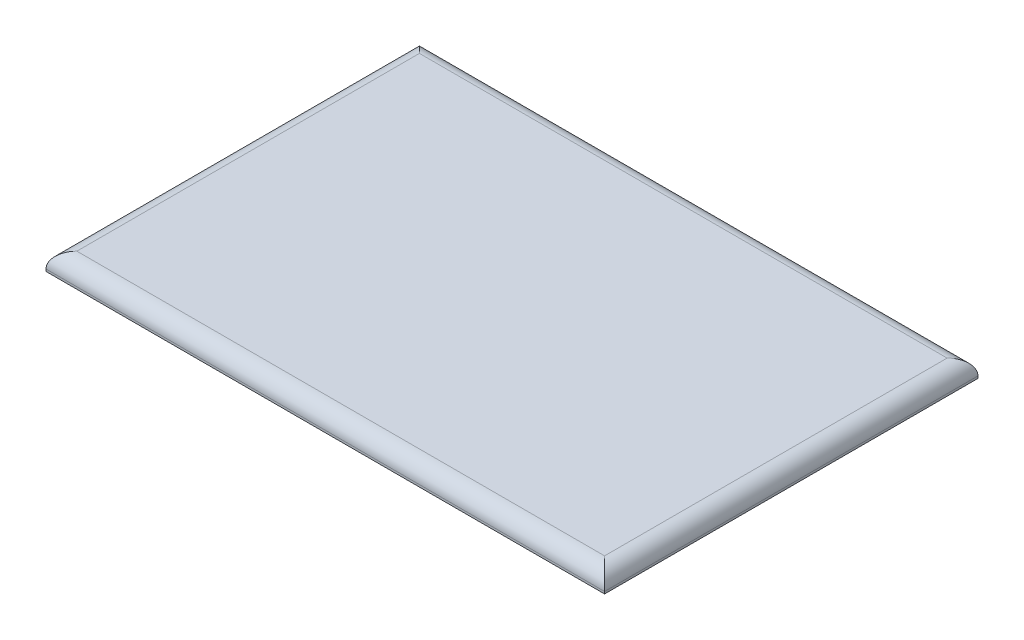
SolidWorks part; units mm, degrees
ref_plane "Front Plane" through (0, 0, 0) normal (0, 0, 1) x (1, 0, 0)
ref_plane "Top Plane" through (0, 0, 0) normal (0, 1, 0) x (1, 0, 0)
ref_plane "Right Plane" through (0, 0, 0) normal (1, 0, 0) x (0, 0, -1)
sketch "Sketch1" plane through (0, 0, 0) normal (0, 1, 0) x (1, 0, 0)
  line L1 (0, 0) -> (91.948, 0)
  line L2 (0, 0) -> (0, 61.468)
  line L3 (0, 61.468) -> (91.948, 61.468)
  line L4 (91.948, 0) -> (91.948, 61.468)
  dimension "D1" = 91.948
  dimension "D2" = 61.468
extrude "Boss-Extrude1" add sketch "Sketch1" along normal blind 2.8956
sketch "Sketch2" plane through (0, 0, 0) normal (0, -1, 0) x (1, 0, 0)
  line L0 (0, -30.734) -> (91.948, -30.734) construction
  line L1 (0, -61.468) -> (0, 0) construction
  line L2 (91.948, 0) -> (91.948, -61.468) construction
  line L3 (33.1216, -47.2948) -> (0, -47.2948)
  line L4 (33.1216, -47.2948) -> (33.1216, -14.1732)
  line L5 (0, -47.2948) -> (0, -14.1732)
  line L6 (33.1216, -14.1732) -> (0, -14.1732)
  line L7 (33.1216, -47.2948) -> (0, -14.1732) construction
  line L8 (0, -47.2948) -> (33.1216, -14.1732) construction
  point P7 (16.5608, -30.734)
  dimension "D1" = 33.1216
extrude "Boss-Extrude2" add sketch "Sketch2" along normal blind 5.3848
fillet "Fillet1" radius 2.54 4 edges at (45.974, 2.8956, -61.468) (91.948, 2.8956, -30.734) (45.974, 2.8956, 0) (0, 2.8956, -30.734)
